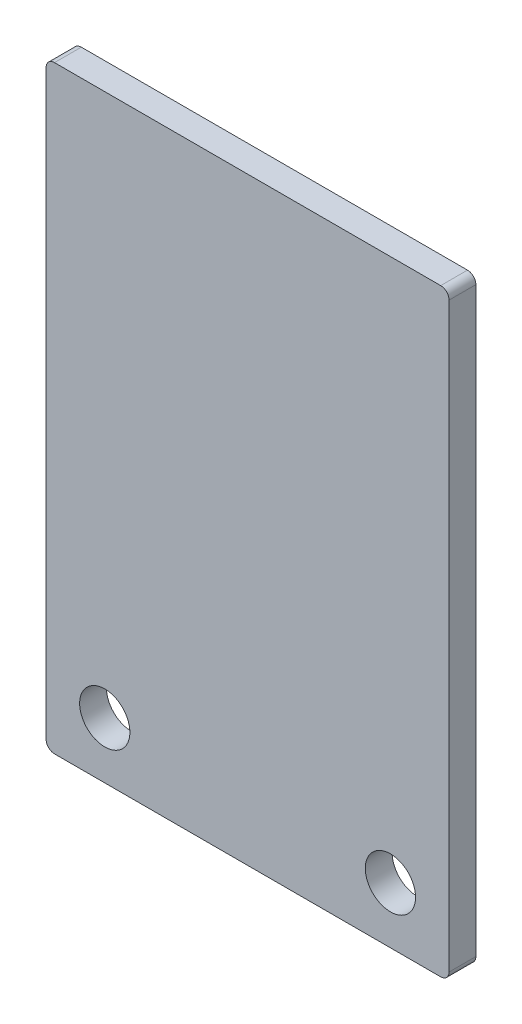
SolidWorks part; units mm, degrees
ref_plane "前视基准面" through (0, 0, 0) normal (0, 0, 1) x (1, 0, 0)
ref_plane "上视基准面" through (0, 0, 0) normal (0, 1, 0) x (1, 0, 0)
ref_plane "右视基准面" through (0, 0, 0) normal (1, 0, 0) x (0, 0, -1)
other "Configuration Table"
sketch "草图1" plane through (0, 0, 0) normal (0, 0, 1) x (1, 0, 0)
  line L0 (0.5, 0) -> (23.55, 0)
  line L1 (24.05, 0.5) -> (24.05, 35.23)
  line L2 (23.55, 35.73) -> (0.5, 35.73)
  line L3 (0, 35.23) -> (0, 0.5)
  arc A0 (23.55, 0) -> (24.05, 0.5) centre (23.55, 0.5) ccw
  arc A1 (24.05, 35.23) -> (23.55, 35.73) centre (23.55, 35.23) ccw
  arc A2 (0.5, 35.73) -> (0, 35.23) centre (0.5, 35.23) ccw
  arc A3 (0, 0.5) -> (0.5, 0) centre (0.5, 0.5) ccw
extrude "Measured_button_PCB" add sketch "草图1" along normal blind 1.6
sketch "草图2" plane through (0, 0, 0) normal (0, 0, 1) x (1, 0, 0)
  circle A0 centre (3.5, 3.36) radius 1.5
  circle A1 centre (20.55, 3.36) radius 1.5
extrude "Measured_button_mount_holes" cut sketch "草图2" along normal blind 2
